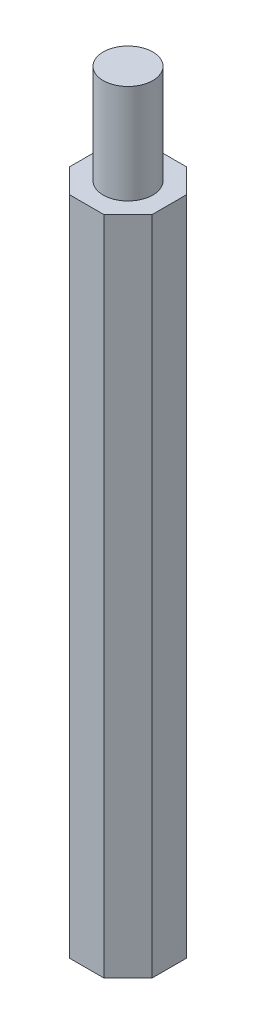
SolidWorks part; units mm, degrees
ref_plane "Plan de face" through (0, 0, 0) normal (0, 0, 1) x (1, 0, 0)
ref_plane "Plan de dessus" through (0, 0, 0) normal (0, 1, 0) x (1, 0, 0)
ref_plane "Plan de droite" through (0, 0, 0) normal (1, 0, 0) x (0, 0, -1)
sketch "Esquisse1" plane through (0, 0, 0) normal (0, 1, 0) x (1, 0, 0)
  line L0 (-1.0355, 2.5) -> (1.0355, 2.5)
  line L1 (1.0355, 2.5) -> (2.5, 1.0355)
  line L2 (2.5, 1.0355) -> (2.5, -1.0355)
  line L3 (2.5, -1.0355) -> (1.0355, -2.5)
  line L4 (1.0355, -2.5) -> (-1.0355, -2.5)
  line L5 (-1.0355, -2.5) -> (-2.5, -1.0355)
  line L6 (-2.5, -1.0355) -> (-2.5, 1.0355)
  line L7 (-2.5, 1.0355) -> (-1.0355, 2.5)
  line L8 (0, 2.5) -> (0, -2.5) construction
  dimension "D1" = 5
extrude "Extrusion1" add sketch "Esquisse1" along normal mid plane 40
sketch "Esquisse2" plane through (0, 20, 0) normal (0, 1, 0) x (1, 0, 0)
  circle A0 centre (0, 0) radius 1.5
  dimension "D1" = 3
extrude "Extrusion2" add sketch "Esquisse2" along normal blind 6
sketch "Esquisse3" plane through (0, -20, 0) normal (0, -1, 0) x (1, 0, 0)
  circle A0 centre (0, 0) radius 1.5
  dimension "D1" = 3
extrude "Enlèv. mat.-Extru.1" cut sketch "Esquisse3" against normal blind 7
